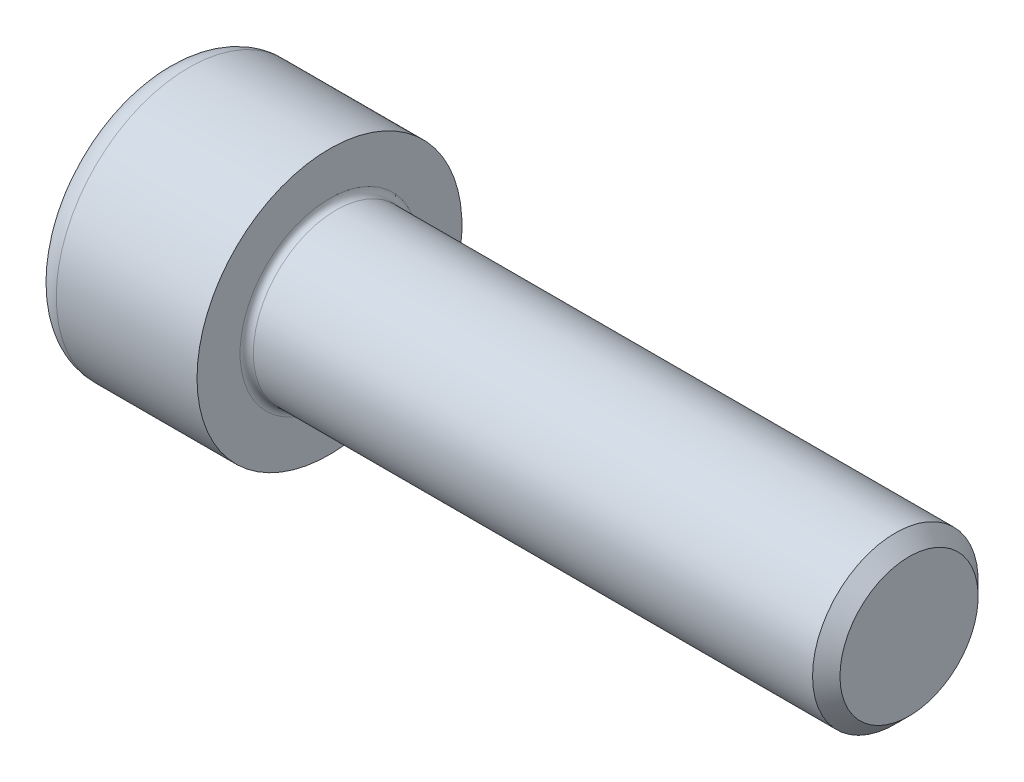
SolidWorks part; units mm, degrees
ref_plane "Plane1" through (0, 0, 0) normal (0, 0, 1) x (1, 0, 0)
ref_plane "Plane2" through (0, 0, 0) normal (0, 1, 0) x (1, 0, 0)
ref_plane "Plane3" through (0, 0, 0) normal (1, 0, 0) x (0, 0, -1)
sketch "BodySke" plane through (0, 0, 0) normal (0, 0, 1) x (1, 0, 0)
  line L0 (0, 0) -> (0, 8)
  line L1 (0, 8) -> (10, 8)
  line L2 (10, 8) -> (10, 5)
  line L3 (10, 5) -> (44.172, 5)
  line L4 (45, 4.172) -> (45, 0)
  line L5 (45, 0) -> (0, 0)
  line L6 (-31.75, 0) -> (127, 0) construction
  line L8 (45, 4.172) -> (44.172, 5)
  line L10 (45, -4.172) -> (44.172, -5) construction
  line L11 (11.5, 9.525) -> (11.5, 3.175) construction
  line L12 (10, 9.525) -> (10, 3.175) construction
  line L13 (-15, 9.525) -> (-15, 3.175) construction
  dimension "Diameter" = 10
  dimension "Head_ht" = 10
  dimension "Length" = 35
  dimension "Body_ch_ang" = 45
  dimension "Head_dia" = 16
  dimension "Minor_dia" = 8.344
  dimension "Advance" = 1.5
  dimension "Thread_nom" = 35
  dimension "Thread_length" = 60
revolve "Base-Revolve" add sketch "BodySke"
cosmetic thread "ThreadCosmetic" [suppressed]
fillet "Fillet1" radius 0.4 1 edges at (10, 0, 5)
fillet "Fillet2" radius 1.5 1 edges at (0, 0, 8)
sketch "Sketch2" plane through (0, 0, 0) normal (0, 0, 1) x (1, 0, 0)
  line L0 (0, 4.0575) -> (5, 4.0575)
  line L1 (5, 4.0575) -> (7.3426, 0)
  line L2 (-31.75, 0) -> (127, 0) construction
  line L3 (7.3426, 0) -> (0, 0)
  line L4 (0, 0) -> (0, 4.0575)
  line L6 (0, 0) -> (47.625, 0) construction
  dimension "D1" = 4.0575
  dimension "D2" = 60
  dimension "Depth" = 5
revolve "Hex-PreBroach" cut sketch "Sketch2" angle 360 about L6
sketch "Sketch3" plane through (0, 0, 0) normal (-1, 0, 0) x (0, 0.5, 0.866)
  line L0 (2.3426, 4.0575) -> (-2.3426, 4.0575)
  line L1 (-2.3426, 4.0575) -> (-4.6852, 0)
  line L2 (2.3426, 4.0575) -> (4.6852, 0)
  line L3 (2.3426, -4.0575) -> (4.6852, 0)
  line L4 (2.3426, -4.0575) -> (-2.3426, -4.0575)
  line L5 (-2.3426, -4.0575) -> (-4.6852, 0)
  dimension "D1" = 4.0575
  dimension "D2" = 4.0575
  dimension "Hex_size" = 8.115
extrude "Hex" cut sketch "Sketch3" against normal blind 5
sketch "ThdSchSke" plane through (0, 0, 0) normal (0, 0, 1) x (1, 0, 0)
  line L0 (14.5, -4.172) -> (13.9202, -5)
  line L1 (14.5, -4.172) -> (15.0798, -5)
  line L2 (15.0798, -5) -> (15.0798, -6.25)
  line L3 (-3.175, 0) -> (5.1513, 0) construction
  line L4 (0, 6.5) -> (0, -6.5) construction
  line L5 (15.0798, -6.25) -> (13.9202, -6.25)
  line L6 (13.9202, -6.25) -> (13.9202, -5)
  dimension "Thread_minor" = 8.344
  dimension "Diameter" = 10
  dimension "Start" = 14.5
  dimension "SideAngle" = 55
  dimension "VeeAngle" = 70
  dimension "Overcut" = 12.5
revolve "ThreadSchematic" [suppressed] cut sketch "ThdSchSke" angle 360 about L3
pattern_linear "ThdSchPat" [suppressed]
equation "\"D2@Sketch3\" = \"Hex_size@Sketch3\" / 2"
equation "\"D1@Sketch3\" = \"Hex_size@Sketch3\" / 2"
equation "\"D1@Sketch2\" = \"Hex_size@Sketch3\" / 2"
equation "\"Thread_minor@ThreadCosmetic\"  =  \"Minor_dia@BodySke\""
equation "\"Depth@Sketch2\" =  \"Key_eng@Hex\""
equation "\"Thread_length@ThreadCosmetic\" = ((sgn( (\"Length@BodySke\" - \"Advance@BodySke\" * 3.0) - \"Thread_nom@BodySke\" )-1)*( (\"Length@BodySke\" - \"Advance@BodySke\" * 3.0) - \"Thread_nom@BodySke\" ))/-2+ \"Thread_nom@BodySke\""
equation "\"Thread_minor@ThdSchSke\" = \"Minor_dia@BodySke\""
equation "\"Diameter@ThdSchSke\" = \"Diameter@BodySke\""
equation "\"Overcut@ThdSchSke\" = \"Diameter@BodySke\" * 1.25"
equation "\"Start@ThdSchSke\" = \"Head_ht@BodySke\" + \"Length@BodySke\" - \"Thread_length@ThreadCosmetic\"  '---Non-countersunk---"
equation "\"Num_threads@ThdSchPat\" = int( \"Thread_length@ThreadCosmetic\" / \"Advance@BodySke\" + 0.999 )  + 1"
equation "\"Advance@ThdSchPat\" = \"Thread_length@ThreadCosmetic\" /  (\"Num_threads@ThdSchPat\" - 1) 'relax it"
equation "\"Num_threads@ThdSchPat\" = \"Num_threads@ThdSchPat\" - sgn( \"Num_threads@ThdSchPat\" - 1) '---chamfered tips only---"
